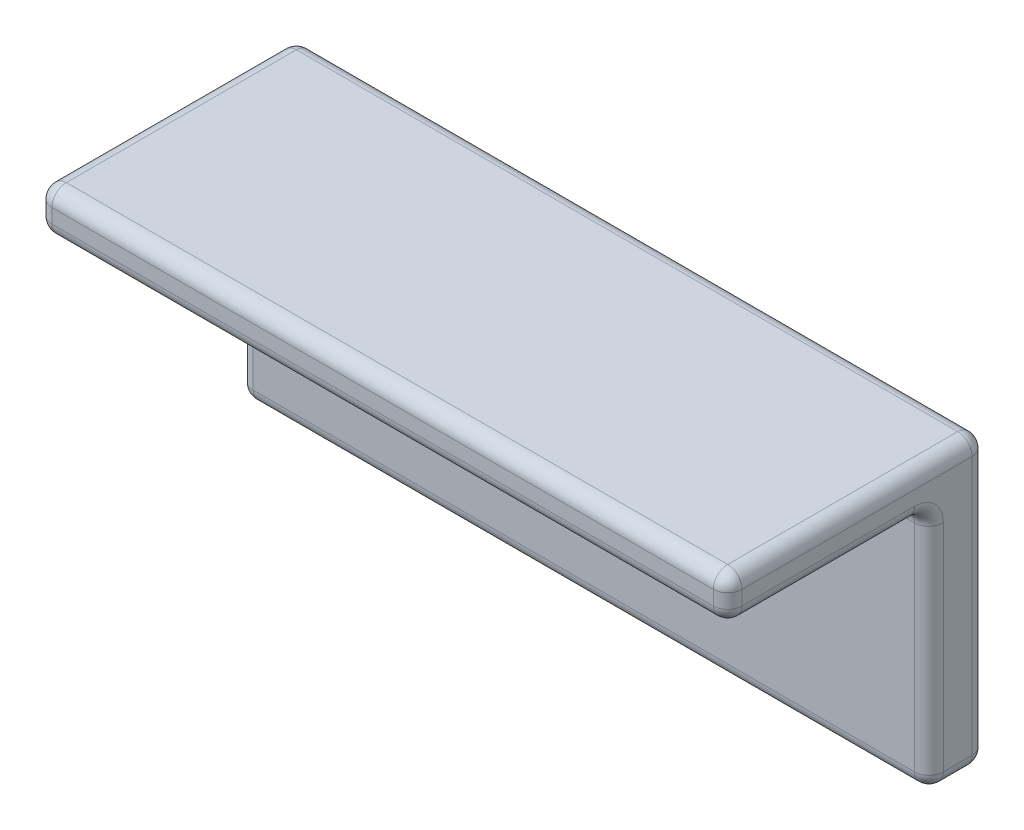
SolidWorks part; units mm, degrees
ref_plane "Alzado" through (0, 0, 0) normal (0, 0, 1) x (1, 0, 0)
ref_plane "Planta" through (0, 0, 0) normal (0, 1, 0) x (1, 0, 0)
ref_plane "Vista lateral" through (0, 0, 0) normal (1, 0, 0) x (0, 0, -1)
sketch "Croquis1" plane through (0, 0, 0) normal (0, 0, 1) x (1, 0, 0)
  line L0 (0, 5) -> (24, 5) construction
  line L1 (0, 0) -> (24, 0)
  line L2 (0, 0) -> (0, 10)
  line L3 (0, 10) -> (24, 10)
  line L4 (24, 0) -> (24, 10)
  circle A0 centre (12, 5) radius 1.75
  dimension "D3" = 3.5
  dimension "D1" = 24
  dimension "D2" = 10
extrude "Saliente-Extruir1" add sketch "Croquis1" along normal blind 2
ref_plane "Plano1" through (0, 0, 2) normal (0, 0, 1) x (1, 0, 0)
sketch "Croquis2" plane through (0, 0, 2) normal (0, 0, 1) x (1, 0, 0)
  line L0 (0, 10) -> (0, 0) construction
  line L1 (24, 10) -> (0, 10)
  line L2 (24, 10) -> (24, 8.5)
  line L3 (24, 8.5) -> (0, 8.5)
  line L4 (0, 10) -> (0, 8.5)
  circle A0 centre (12, 5) radius 3.5 construction
  dimension "D1" = 7
extrude "Saliente-Extruir2" add sketch "Croquis2" along normal blind 7
fillet "Redondeo1" radius 0.5 20 edges at (0, 0, 1) (13.75, 5, 0) (12, 0, 0) (0, 5, 0) (24, 0, 1) (24, 5, 0) (24, 10, 4.5) (0, 10, 4.5) (12, 10, 0) (0, 9.25, 9) (12, 10, 9) (24, 9.25, 9) (0, 8.5, 5.5) (12, 8.5, 9) (24, 8.5, 5.5) (24, 4.25, 2) (12, 0, 2) (0, 4.25, 2) (12, 8.5, 2) (13.75, 5, 2)
